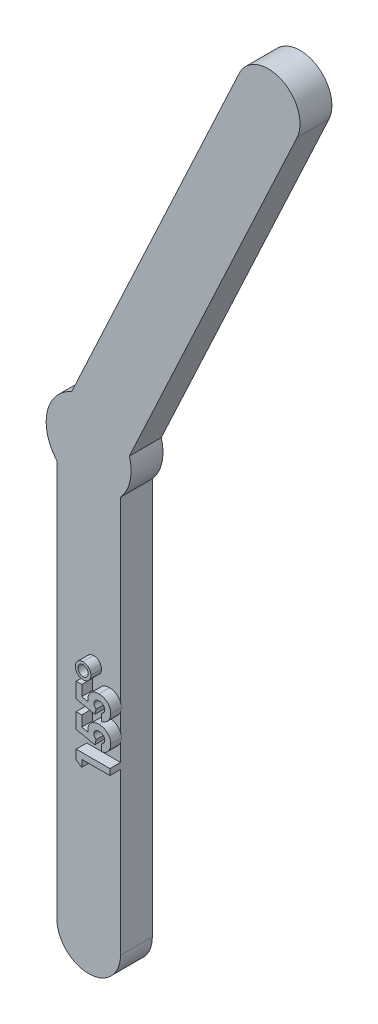
SolidWorks part; units mm, degrees
ref_plane "Front Plane" through (0, 0, 0) normal (0, 0, 1) x (1, 0, 0)
ref_plane "Top Plane" through (0, 0, 0) normal (0, 1, 0) x (1, 0, 0)
ref_plane "Right Plane" through (0, 0, 0) normal (1, 0, 0) x (0, 0, -1)
sketch "Sketch2" plane through (0, 0, 0) normal (0, 0, 1) x (1, 0, 0)
  line L0 (0, 0) -> (0, -40) construction
  line L1 (0, 0) -> (16.9047, 36.2523) construction
  line L2 (14.1858, 37.5202) -> (19.6237, 34.9845) construction
  line L3 (-3, -40) -> (3, -40) construction
  line L4 (-3, -40) -> (-3, -2.6458)
  line L5 (3, -40) -> (3, -2.6458)
  line L6 (14.1858, 37.5202) -> (-1.6008, 3.6657)
  line L7 (19.6237, 34.9845) -> (3.8371, 1.13)
  arc A0 (-1.6008, 3.6657) -> (-3, -2.6458) centre (0, 0) ccw
  arc A1 (-3, -40) -> (3, -40) centre (0, -40) ccw
  arc A2 (14.1858, 37.5202) -> (19.6237, 34.9845) centre (16.9047, 36.2523) cw
  arc A3 (3, -2.6458) -> (3.8371, 1.13) centre (0, 0) ccw
  point P12 (16.9047, 36.2523)
  dimension "D3" = 3
  dimension "D4" = 8
  dimension "D1" = 40
  dimension "D2" = 155
extrude "Boss-Extrude1" add sketch "Sketch2" along normal blind 3
sketch "Sketch3" plane through (0, 0, 3) normal (0, 0, 1) x (1, 0, 0)
  text T0 "<b>155°</b>"
extrude "Boss-Extrude2" add sketch "Sketch3" along normal blind 1
